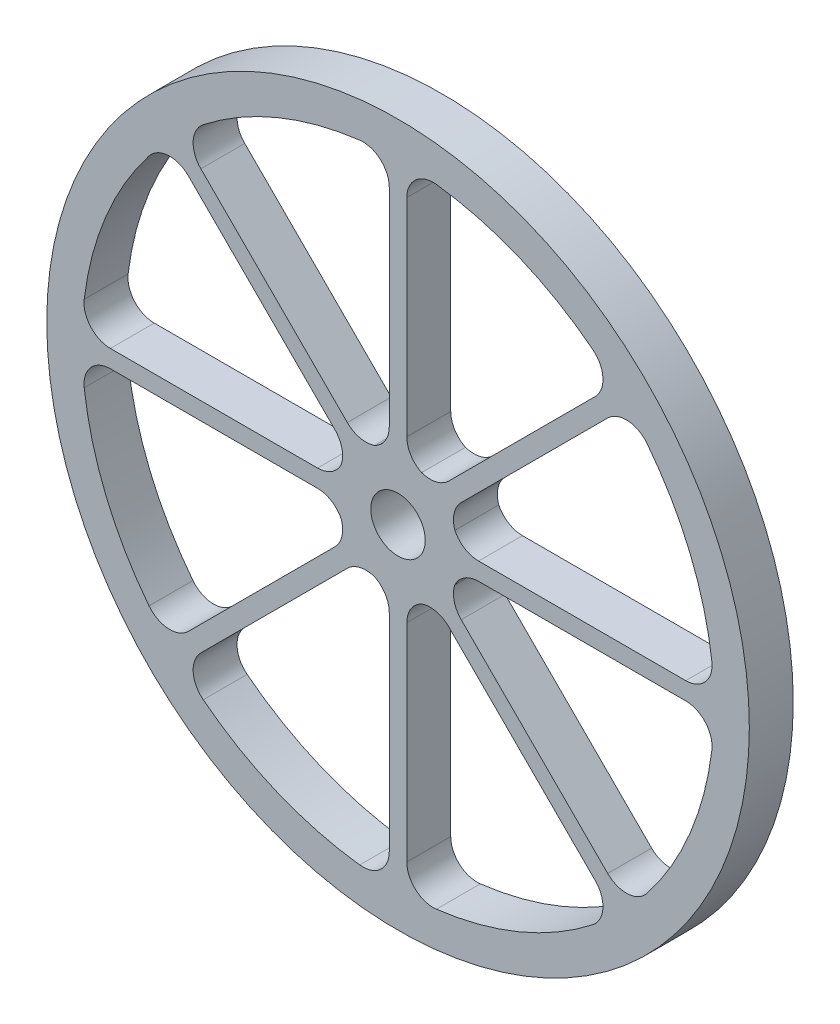
SolidWorks part; units mm, degrees
ref_plane "前视基准面" through (0, 0, 0) normal (0, 0, 1) x (1, 0, 0)
ref_plane "上视基准面" through (0, 0, 0) normal (0, 1, 0) x (1, 0, 0)
ref_plane "右视基准面" through (0, 0, 0) normal (1, 0, 0) x (0, 0, -1)
sketch "Model" plane through (0, 0, 0) normal (0, 0, 1) x (1, 0, 0)
  line L0 (57.6719, 56.1373) -> (57.6719, 79.7288)
  line L1 (36.2166, 70.8417) -> (52.8983, 54.16)
  line L2 (64.4456, 54.16) -> (81.1273, 70.8417)
  line L3 (59.6719, 79.7288) -> (59.6719, 56.1373)
  line L4 (67.8371, 47.9722) -> (91.4286, 47.9722)
  line L5 (82.5415, 69.4275) -> (65.8598, 52.7458)
  line L6 (65.8598, 41.1985) -> (82.5415, 24.5168)
  line L7 (91.4286, 45.9722) -> (67.8371, 45.9722)
  line L8 (59.6719, 37.807) -> (59.6719, 14.2155)
  line L9 (81.1273, 23.1026) -> (64.4456, 39.7843)
  line L10 (52.8983, 39.7843) -> (36.2166, 23.1026)
  line L11 (57.6719, 14.2155) -> (57.6719, 37.807)
  line L12 (49.5068, 45.9722) -> (25.9153, 45.9722)
  line L13 (34.8024, 24.5168) -> (51.4841, 41.1985)
  line L14 (51.4841, 52.7458) -> (34.8024, 69.4275)
  line L15 (25.9153, 47.9722) -> (49.5068, 47.9722)
  circle A0 centre (58.6719, 46.9722) radius 40
  circle A1 centre (58.6719, 46.9722) radius 3.1
  arc A2 (55.9916, 53.4431) -> (57.6719, 56.1373) centre (54.6719, 56.1373) ccw
  arc A3 (57.6719, 79.7288) -> (54.3083, 82.7067) centre (54.6719, 79.7288) ccw
  arc A4 (54.3083, 82.7067) -> (36.4893, 75.3259) centre (58.6719, 46.9722) ccw
  arc A5 (36.4893, 75.3259) -> (36.2166, 70.8417) centre (38.3379, 72.9631) ccw
  arc A6 (52.8983, 54.16) -> (55.9916, 53.4431) centre (55.0196, 56.2813) ccw
  arc A7 (61.3523, 53.4431) -> (64.4456, 54.16) centre (62.3242, 56.2813) ccw
  arc A8 (81.1273, 70.8417) -> (80.8545, 75.3259) centre (79.006, 72.9631) ccw
  arc A9 (80.8545, 75.3259) -> (63.0356, 82.7067) centre (58.6719, 46.9722) ccw
  arc A10 (63.0356, 82.7067) -> (59.6719, 79.7288) centre (62.6719, 79.7288) ccw
  arc A11 (59.6719, 56.1373) -> (61.3523, 53.4431) centre (62.6719, 56.1373) ccw
  arc A12 (65.1429, 49.6525) -> (67.8371, 47.9722) centre (67.8371, 50.9722) ccw
  arc A13 (91.4286, 47.9722) -> (94.4065, 51.3358) centre (91.4286, 50.9722) ccw
  arc A14 (94.4065, 51.3358) -> (87.0256, 69.1548) centre (58.6719, 46.9722) ccw
  arc A15 (87.0256, 69.1548) -> (82.5415, 69.4275) centre (84.6628, 67.3062) ccw
  arc A16 (65.8598, 52.7458) -> (65.1429, 49.6525) centre (67.9811, 50.6245) ccw
  arc A17 (65.1429, 44.2918) -> (65.8598, 41.1985) centre (67.9811, 43.3199) ccw
  arc A18 (82.5415, 24.5168) -> (87.0256, 24.7896) centre (84.6628, 26.6381) ccw
  arc A19 (87.0256, 24.7896) -> (94.4065, 42.6085) centre (58.6719, 46.9722) ccw
  arc A20 (94.4065, 42.6085) -> (91.4286, 45.9722) centre (91.4286, 42.9722) ccw
  arc A21 (67.8371, 45.9722) -> (65.1429, 44.2918) centre (67.8371, 42.9722) ccw
  arc A22 (61.3523, 40.5012) -> (59.6719, 37.807) centre (62.6719, 37.807) ccw
  arc A23 (59.6719, 14.2155) -> (63.0356, 11.2376) centre (62.6719, 14.2155) ccw
  arc A24 (63.0356, 11.2376) -> (80.8545, 18.6185) centre (58.6719, 46.9722) ccw
  arc A25 (80.8545, 18.6185) -> (81.1273, 23.1026) centre (79.006, 20.9813) ccw
  arc A26 (64.4456, 39.7843) -> (61.3523, 40.5012) centre (62.3242, 37.663) ccw
  arc A27 (55.9916, 40.5012) -> (52.8983, 39.7843) centre (55.0196, 37.663) ccw
  arc A28 (36.2166, 23.1026) -> (36.4893, 18.6185) centre (38.3379, 20.9813) ccw
  arc A29 (36.4893, 18.6185) -> (54.3083, 11.2376) centre (58.6719, 46.9722) ccw
  arc A30 (54.3083, 11.2376) -> (57.6719, 14.2155) centre (54.6719, 14.2155) ccw
  arc A31 (57.6719, 37.807) -> (55.9916, 40.5012) centre (54.6719, 37.807) ccw
  arc A32 (52.201, 44.2918) -> (49.5068, 45.9722) centre (49.5068, 42.9722) ccw
  arc A33 (25.9153, 45.9722) -> (22.9374, 42.6085) centre (25.9153, 42.9722) ccw
  arc A34 (22.9374, 42.6085) -> (30.3182, 24.7896) centre (58.6719, 46.9722) ccw
  arc A35 (30.3182, 24.7896) -> (34.8024, 24.5168) centre (32.681, 26.6381) ccw
  arc A36 (51.4841, 41.1985) -> (52.201, 44.2918) centre (49.3628, 43.3199) ccw
  arc A37 (52.201, 49.6525) -> (51.4841, 52.7458) centre (49.3628, 50.6245) ccw
  arc A38 (34.8024, 69.4275) -> (30.3182, 69.1548) centre (32.681, 67.3062) ccw
  arc A39 (30.3182, 69.1548) -> (22.9374, 51.3358) centre (58.6719, 46.9722) ccw
  arc A40 (22.9374, 51.3358) -> (25.9153, 47.9722) centre (25.9153, 50.9722) ccw
  arc A41 (49.5068, 47.9722) -> (52.201, 49.6525) centre (49.5068, 50.9722) ccw
extrude "凸台-拉伸1" add sketch "Model" along normal blind 5
